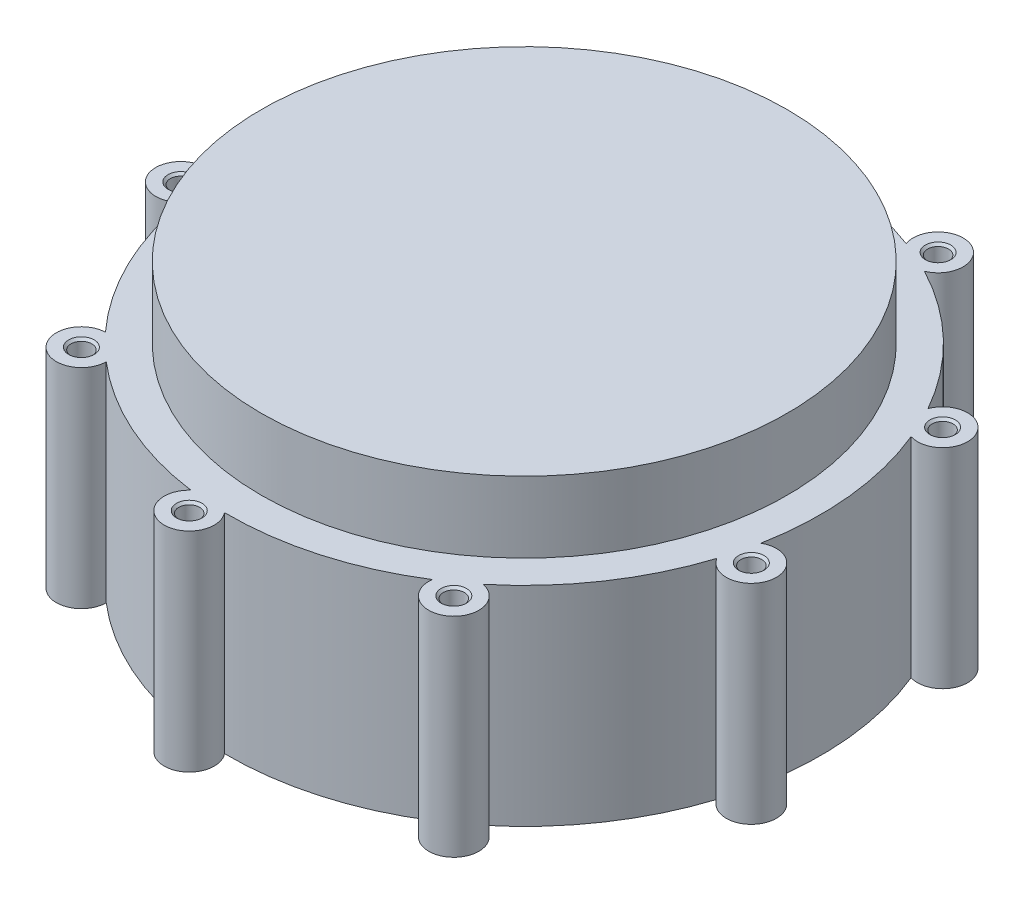
SolidWorks part; units mm, degrees
ref_plane "前视基准面" through (0, 0, 0) normal (0, 0, 1) x (1, 0, 0)
ref_plane "上视基准面" through (0, 0, 0) normal (0, 1, 0) x (1, 0, 0)
ref_plane "右视基准面" through (0, 0, 0) normal (1, 0, 0) x (0, 0, -1)
other "Configuration Table"
sketch "草图1" plane through (0, 0, 0) normal (0, 1, 0) x (1, 0, 0)
  line L0 (-58.3719, 0) -> (67.7056, 0) construction
  line L1 (0, 43.1712) -> (0, -44.4703) construction
  circle A0 centre (0, 0) radius 35.5
  circle A1 centre (0, 0) radius 37.5 construction
  circle A2 centre (-10.2425, 36.0741) radius 3
  circle A3 centre (15.3418, 34.2181) radius 3
  circle A4 centre (33.7475, 16.3511) radius 3
  circle A5 centre (36.3623, -9.1668) radius 3
  circle A6 centre (21.9628, -30.3954) radius 3
  circle A7 centre (-2.7133, -37.4017) radius 3
  circle A8 centre (-26.1199, -26.9073) radius 3
  circle A9 centre (-37.3047, -3.8227) radius 3
  circle A10 centre (-31.0342, 21.0506) radius 3
  point P29 (0, 0)
  dimension "D1" = 71
  dimension "D2" = 75
  dimension "D3" = 6
  dimension "D4" = 9
extrude "凸台-拉伸1" add sketch "草图1" along normal blind 25 contours A10 A0 A9 A8 A7 A6 A5 A4 A3 A2 | A0 A9 | A0 A9 | A0 A8 | A0 A8 | A0 A7 | A0 A7 | A0 A6 | A0 A6 | A0 A5 | A0 A5 | A0 A4 | A0 A4 | A0 A3 | A0 A3 | A0 A2 | A0 A2 | A0 A10 | A0 A10
sketch "草图2" plane through (0, 0, 0) normal (0, -1, 0) x (1, 0, 0)
  arc A0 (-23.12, 26.9391) -> (-26.2407, 23.9097) centre (-26.1199, 26.9073) ccw construction
  arc A1 (-23.12, 26.9391) -> (-26.2407, 23.9097) centre (-26.1199, 26.9073) ccw
  arc A2 (-26.2407, 23.9097) -> (-35.0271, 5.7753) centre (0, 0) ccw construction
  arc A3 (-26.2407, 23.9097) -> (-35.0271, 5.7753) centre (0, 0) ccw
  circle A4 centre (-26.1199, 26.9073) radius 1.5
  circle A5 centre (-2.7133, 37.4017) radius 1.5
  circle A6 centre (21.9628, 30.3954) radius 1.5
  circle A7 centre (36.3623, 9.1668) radius 1.5
  circle A8 centre (33.7475, -16.3511) radius 1.5
  circle A9 centre (15.3418, -34.2181) radius 1.5
  circle A10 centre (-10.2425, -36.0741) radius 1.5
  circle A11 centre (-31.0342, -21.0506) radius 1.5
  circle A12 centre (-37.3047, 3.8227) radius 1.5
  arc A22 (-28.1031, -21.6902) -> (-11.7699, -33.4921) centre (0, 0) ccw
  arc A23 (-11.7699, -33.4921) -> (-7.5861, -34.68) centre (-10.2425, -36.0741) ccw
  arc A24 (-7.5861, -34.68) -> (12.512, -33.222) centre (0, 0) ccw
  arc A25 (12.512, -33.222) -> (16.4806, -31.4426) centre (15.3418, -34.2181) ccw
  arc A26 (16.4806, -31.4426) -> (30.9394, -17.4069) centre (0, 0) ccw
  arc A27 (30.9394, -17.4069) -> (32.8358, -13.4929) centre (33.7475, -16.3511) ccw
  arc A28 (32.8358, -13.4929) -> (34.8899, 6.553) centre (0, 0) ccw
  arc A29 (34.8899, 6.553) -> (33.8268, 10.7703) centre (36.3623, 9.1668) ccw
  arc A30 (33.8268, 10.7703) -> (22.5151, 27.4467) centre (0, 0) ccw
  arc A31 (22.5151, 27.4467) -> (18.9898, 29.9939) centre (21.9628, 30.3954) ccw
  arc A32 (18.9898, 29.9939) -> (-0.3949, 35.4978) centre (0, 0) ccw
  arc A33 (-0.3949, 35.4978) -> (-4.7327, 35.1831) centre (-2.7133, 37.4017) ccw
  arc A34 (-4.7327, 35.1831) -> (-23.12, 26.9391) centre (0, 0) ccw
  arc A35 (-23.12, 26.9391) -> (-26.2407, 23.9097) centre (-26.1199, 26.9073) ccw
  arc A36 (-26.2407, 23.9097) -> (-35.0271, 5.7753) centre (0, 0) ccw
  arc A37 (-35.0271, 5.7753) -> (-35.4704, 1.4487) centre (-37.3047, 3.8227) ccw
  arc A38 (-35.4704, 1.4487) -> (-30.5446, -18.0909) centre (0, 0) ccw
  arc A39 (-30.5446, -18.0909) -> (-28.1031, -21.6902) centre (-31.0342, -21.0506) ccw
  arc A40 (-28.1031, -21.6902) -> (-11.7699, -33.4921) centre (0, 0) ccw
  arc A41 (-11.7699, -33.4921) -> (-7.5861, -34.68) centre (-10.2425, -36.0741) ccw
  arc A42 (-7.5861, -34.68) -> (12.512, -33.222) centre (0, 0) ccw
  arc A43 (12.512, -33.222) -> (16.4806, -31.4426) centre (15.3418, -34.2181) ccw
  arc A44 (16.4806, -31.4426) -> (30.9394, -17.4069) centre (0, 0) ccw
  arc A45 (30.9394, -17.4069) -> (32.8358, -13.4929) centre (33.7475, -16.3511) ccw
  arc A46 (32.8358, -13.4929) -> (34.8899, 6.553) centre (0, 0) ccw
  arc A47 (34.8899, 6.553) -> (33.8268, 10.7703) centre (36.3623, 9.1668) ccw
  arc A48 (33.8268, 10.7703) -> (22.5151, 27.4467) centre (0, 0) ccw
  arc A49 (22.5151, 27.4467) -> (18.9898, 29.9939) centre (21.9628, 30.3954) ccw
  arc A50 (18.9898, 29.9939) -> (-0.3949, 35.4978) centre (0, 0) ccw
  arc A51 (-0.3949, 35.4978) -> (-4.7327, 35.1831) centre (-2.7133, 37.4017) ccw
  arc A52 (-4.7327, 35.1831) -> (-23.12, 26.9391) centre (0, 0) ccw
  arc A53 (-23.12, 26.9391) -> (-26.2407, 23.9097) centre (-26.1199, 26.9073) ccw
  arc A54 (-26.2407, 23.9097) -> (-35.0271, 5.7753) centre (0, 0) ccw
  arc A55 (-35.0271, 5.7753) -> (-35.4704, 1.4487) centre (-37.3047, 3.8227) ccw
  arc A56 (-35.4704, 1.4487) -> (-30.5446, -18.0909) centre (0, 0) ccw
  arc A57 (-30.5446, -18.0909) -> (-28.1031, -21.6902) centre (-31.0342, -21.0506) ccw
  point P60 (0, 0)
  dimension "D2" = 9
  dimension "D1" = 0
hole_wizard "M3 螺纹孔1" positions "3D草图2" profile "草图6" tap size "M3" standard "GB"
sketch3d "3D草图2"
  point P0 (-26.1199, 0, 26.9073)
  point P3 (-2.7133, 0, 37.4017)
  point P6 (21.9628, 0, 30.3954)
  point P9 (36.3623, 0, 9.1668)
  point P12 (33.7475, 0, -16.3511)
  point P15 (15.3418, 0, -34.2181)
  point P18 (-10.2425, 0, -36.0741)
  point P21 (-31.0342, 0, -21.0506)
  point P24 (-37.3047, 0, 3.8227)
sketch "草图6" plane through (-26.1199, 0, 26.9073) normal (1, 0, 0) x (0, 0, -1)
  line L0 (0, 0) -> (0, 8.7511)
  line L1 (0, 8.7511) -> (1.25, 8)
  line L2 (1.25, 8) -> (1.25, 0.275)
  line L3 (1.25, 0.275) -> (1.525, 0)
  line L5 (1.525, 0) -> (0, 0)
  line L6 (-1.25, 0.275) -> (-1.525, 0) construction
  line L10 (0, 8.7511) -> (-1.25, 8) construction
  line L11 (0, -6.35) -> (0, 107.95) construction
  dimension "螺纹孔钻头直径" = 2.5
  dimension "螺纹孔钻头深度" = 8
  dimension "近端锥形沉头孔直径" = 3.05
  dimension "近端锥形沉头孔角度" = 90
  dimension "导头角度" = 118
cosmetic thread "孔螺蚊线1" parameters "D1"=8, "D2"=3
cosmetic thread "孔螺蚊线2" parameters "D1"=8, "D2"=3
cosmetic thread "孔螺蚊线3" parameters "D1"=8, "D2"=3
cosmetic thread "孔螺蚊线4" parameters "D1"=8, "D2"=3
cosmetic thread "孔螺蚊线5" parameters "D1"=8, "D2"=3
cosmetic thread "孔螺蚊线6" parameters "D1"=8, "D2"=3
cosmetic thread "孔螺蚊线7" parameters "D1"=8, "D2"=3
cosmetic thread "孔螺蚊线8" parameters "D1"=8, "D2"=3
cosmetic thread "孔螺蚊线9" parameters "D1"=8, "D2"=3
sketch "草图7" plane through (0, 0, 0) normal (0, -1, 0) x (1, 0, 0)
  circle A0 centre (0, 0) radius 21.5
  circle A1 centre (0, 0) radius 18
  dimension "D1" = 43
  dimension "D2" = 36
extrude "凸台-拉伸3" add sketch "草图7" along normal blind 2
sketch "草图8" plane through (0, 0, 0) normal (0, -1, 0) x (1, 0, 0)
  circle A1 centre (0, 0) radius 18
  circle A2 centre (0, 0) radius 18
  dimension "D1" = 0
extrude "切除-拉伸2" cut sketch "草图8" against normal blind 5 contours A2
sketch "草图9" plane through (0, 5, 0) normal (0, -1, 0) x (1, 0, 0)
  circle A0 centre (0, 0) radius 2
  dimension "D1" = 4
extrude "切除-拉伸3" cut sketch "草图9" against normal blind 1
sketch "草图11" plane through (0, 25, 0) normal (0, 1, 0) x (1, 0, 0)
  circle A0 centre (0, 0) radius 31.5
  dimension "D1" = 63
extrude "凸台-拉伸4" add sketch "草图11" along normal blind 8.5 contours A0
sketch "草图12" plane through (0, 25, 0) normal (0, 1, 0) x (1, 0, 0)
  circle A0 centre (-31.0342, 21.0506) radius 1.5 construction
  circle A1 centre (-31.0342, 21.0506) radius 1.5
  circle A2 centre (-37.3047, -3.8227) radius 1.5 construction
  circle A3 centre (-26.1199, -26.9073) radius 1.5 construction
  circle A4 centre (-2.7133, -37.4017) radius 1.5 construction
  circle A5 centre (21.9628, -30.3954) radius 1.5 construction
  circle A6 centre (36.3623, -9.1668) radius 1.5 construction
  circle A7 centre (33.7475, 16.3511) radius 1.5 construction
  circle A8 centre (15.3418, 34.2181) radius 1.5 construction
  circle A9 centre (-10.2425, 36.0741) radius 1.5 construction
  circle A10 centre (-37.3047, -3.8227) radius 1.5
  circle A11 centre (-26.1199, -26.9073) radius 1.5
  circle A12 centre (-2.7133, -37.4017) radius 1.5
  circle A13 centre (21.9628, -30.3954) radius 1.5
  circle A14 centre (36.3623, -9.1668) radius 1.5
  circle A15 centre (33.7475, 16.3511) radius 1.5
  circle A16 centre (15.3418, 34.2181) radius 1.5
  circle A17 centre (-10.2425, 36.0741) radius 1.5
hole_wizard "M3 螺纹孔4" positions "草图19" profile "草图20" tap size "M3" standard "GB"
sketch "草图19" plane through (0, 25, 0) normal (0, 1, 0) x (1, 0, 0)
  point P0 (-31.0342, 21.0506)
  point P3 (-37.3047, -3.8227)
  point P6 (-26.1199, -26.9073)
  point P9 (-2.7133, -37.4017)
  point P12 (21.9628, -30.3954)
  point P15 (36.3623, -9.1668)
  point P18 (33.7475, 16.3511)
  point P21 (15.3418, 34.2181)
  point P24 (-10.2425, 36.0741)
sketch "草图20" plane through (-31.0342, 25, -21.0506) normal (1, 0, 0) x (0, 0, 1)
  line L0 (0, 0) -> (0, 8.7511)
  line L1 (0, 8.7511) -> (1.25, 8)
  line L2 (1.25, 8) -> (1.25, 0.275)
  line L3 (1.25, 0.275) -> (1.525, 0)
  line L5 (1.525, 0) -> (0, 0)
  line L6 (-1.25, 0.275) -> (-1.525, 0) construction
  line L10 (0, 8.7511) -> (-1.25, 8) construction
  line L11 (0, -6.35) -> (0, 107.95) construction
  dimension "螺纹孔钻头直径" = 2.5
  dimension "螺纹孔钻头深度" = 8
  dimension "近端锥形沉头孔直径" = 3.05
  dimension "近端锥形沉头孔角度" = 90
  dimension "导头角度" = 118
cosmetic thread "孔螺蚊线12" parameters "D1"=8, "D2"=3
cosmetic thread "孔螺蚊线13" parameters "D1"=8, "D2"=3
cosmetic thread "孔螺蚊线14" parameters "D1"=8, "D2"=3
cosmetic thread "孔螺蚊线15" parameters "D1"=8, "D2"=3
cosmetic thread "孔螺蚊线16" parameters "D1"=8, "D2"=3
cosmetic thread "孔螺蚊线17" parameters "D1"=8, "D2"=3
cosmetic thread "孔螺蚊线18" parameters "D1"=8, "D2"=3
cosmetic thread "孔螺蚊线19" parameters "D1"=8, "D2"=3
cosmetic thread "孔螺蚊线20" parameters "D1"=8, "D2"=3
